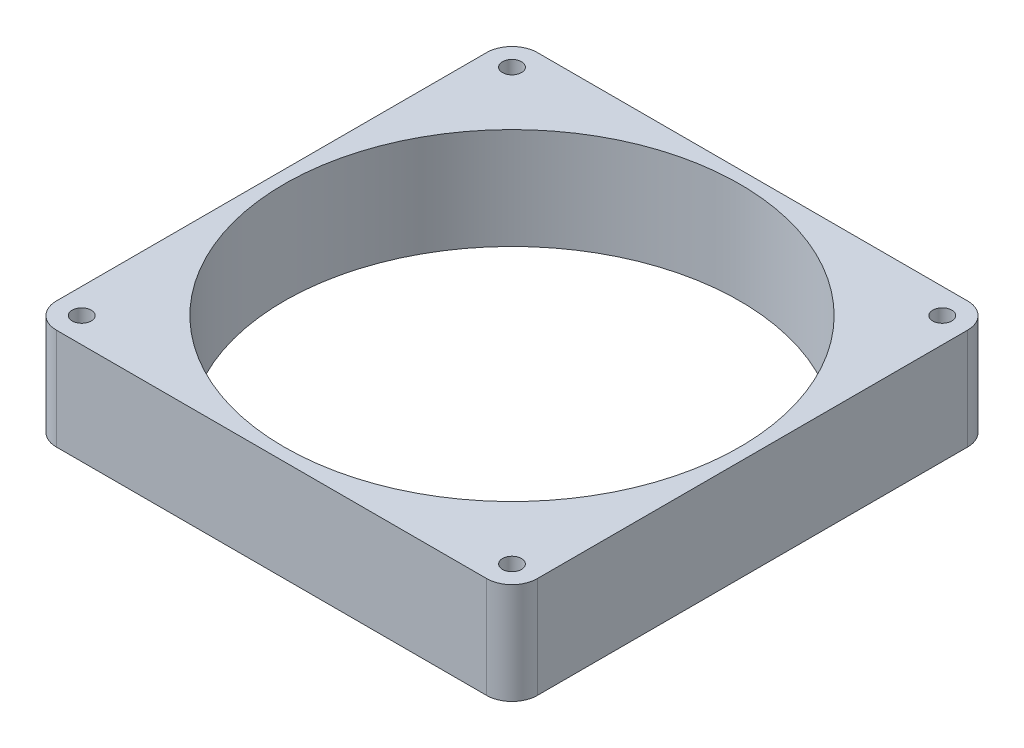
SolidWorks part; units mm, degrees
ref_plane "Front Plane" through (0, 0, 0) normal (0, 0, 1) x (1, 0, 0)
ref_plane "Top Plane" through (0, 0, 0) normal (0, 1, 0) x (1, 0, 0)
ref_plane "Right Plane" through (0, 0, 0) normal (1, 0, 0) x (0, 0, -1)
sketch "Sketch1" plane through (0, 0, 0) normal (0, 1, 0) x (1, 0, 0)
  line L0 (-32.5912, 19.8994) -> (88.0588, 19.8994)
  line L1 (88.0588, 19.8994) -> (88.0588, -100.7506)
  line L2 (-32.5912, 19.8994) -> (-32.5912, -100.7506)
  line L3 (-32.5912, -100.7506) -> (88.0588, -100.7506)
  dimension "D1" = 120.65
  dimension "D2" = 120.65
extrude "Boss-Extrude1" add sketch "Sketch1" along normal blind 25.4
fillet "Fillet1" radius 6.35 1 edges at (-32.5912, 12.7, 100.7506)
fillet "Fillet2" radius 6.35 3 edges at (-32.5912, 12.7, -19.8994) (88.0588, 12.7, -19.8994) (88.0588, 12.7, 100.7506)
sketch "Sketch2" plane through (0, 25.4, 0) normal (0, 1, 0) x (1, 0, 0)
  line L0 (-32.5912, 13.5494) -> (-32.5912, -94.4006) construction
  line L1 (-26.2412, -100.7506) -> (81.7088, -100.7506) construction
  line L2 (88.0588, -94.4006) -> (88.0588, 13.5494) construction
  line L3 (81.7088, 19.8994) -> (-26.2412, 19.8994) construction
  circle A0 centre (-26.2412, -94.4006) radius 2.3813
  circle A1 centre (-26.2412, 13.5494) radius 2.3813
  circle A2 centre (81.7088, 13.5494) radius 2.3813
  circle A3 centre (81.7088, -94.4006) radius 2.3813
  point P17 (0, 0)
  point P18 (0, 0)
  dimension "D1" = 6.35
  dimension "D2" = 6.35
  dimension "D3" = 6.35
  dimension "D4" = 6.35
  dimension "D5" = 6.35
  dimension "D6" = 6.35
  dimension "D7" = 6.35
  dimension "D8" = 6.35
extrude "Cut-Extrude1" cut sketch "Sketch2" against normal through all
sketch "Sketch4" plane through (0, 25.4, 0) normal (0, 1, 0) x (1, 0, 0)
  line L0 (-32.5912, 13.5494) -> (-32.5912, -94.4006) construction
  line L1 (-26.2412, -100.7506) -> (81.7088, -100.7506) construction
  circle A0 centre (27.7338, -40.4256) radius 57.15
  dimension "D1" = 60.325
  dimension "D3" = 114.3
  dimension "D2" = 60.325
extrude "Cut-Extrude2" cut sketch "Sketch4" against normal blind 25.4
